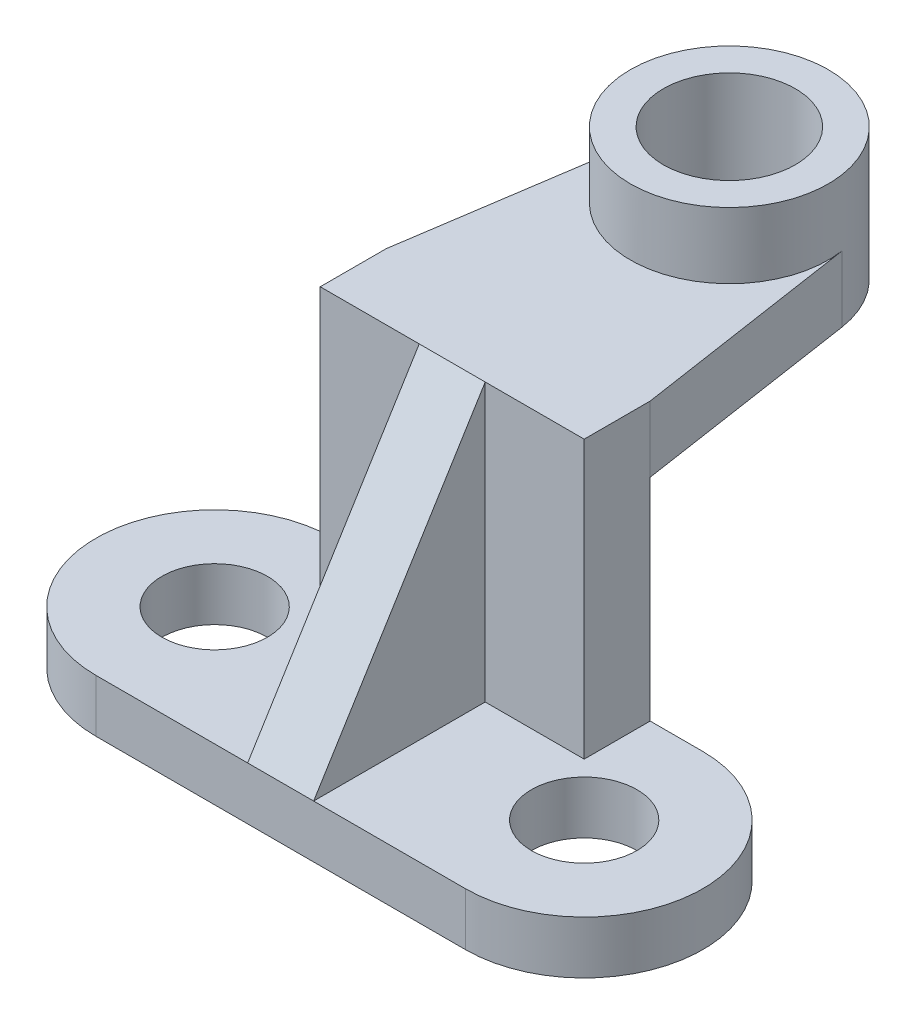
SolidWorks part; units mm, degrees
ref_plane "Front Plane" through (0, 0, 0) normal (0, 0, 1) x (1, 0, 0)
ref_plane "Top Plane" through (0, 0, 0) normal (0, 1, 0) x (1, 0, 0)
ref_plane "Right Plane" through (0, 0, 0) normal (1, 0, 0) x (0, 0, -1)
sketch "Sketch1" plane through (0, 0, 0) normal (0, 1, 0) x (1, 0, 0)
  line L0 (-28, 0) -> (28, 0) construction
  line L1 (-28, 18) -> (28, 18)
  line L2 (-28, -18) -> (28, -18)
  arc A0 (-28, 18) -> (-28, -18) centre (-28, 0) ccw
  arc A1 (28, -18) -> (28, 18) centre (28, 0) ccw
  circle A2 centre (-28, 0) radius 8
  circle A3 centre (28, 0) radius 8
  point P3 (0, 0)
  dimension "D1" = 18
  dimension "D3" = 16
  dimension "D2" = 56
extrude "Boss-Extrude1" add sketch "Sketch1" along normal mid plane 8
sketch "Sketch2" plane through (0, 4, 0) normal (0, 1, 0) x (1, 0, 0)
  line L0 (28, 18) -> (-28, 18) construction
  line L1 (-20, 8) -> (20, 8)
  line L2 (-20, 8) -> (-20, 18)
  line L3 (-20, 18) -> (20, 18)
  line L4 (20, 8) -> (20, 18)
  line L5 (-20, 8) -> (20, 18) construction
  line L6 (-20, 18) -> (20, 8) construction
  point P0 (0, 13)
  dimension "D1" = 40
  dimension "D2" = 10
extrude "Boss-Extrude2" add sketch "Sketch2" along normal blind 32
ref_plane "Plane1" through (0, 46, 0) normal (0, 1, 0) x (1, 0, 0)
sketch "Sketch3" plane through (0, 46, 0) normal (0, 1, 0) x (1, 0, 0)
  circle A0 centre (0, 50) radius 15
  circle A1 centre (0, 50) radius 10
  dimension "D1" = 30
  dimension "D2" = 20
  dimension "D3" = 50
extrude "Boss-Extrude3" add sketch "Sketch3" along normal mid plane 20 separate body
sketch "Sketch4" plane through (0, 46, 0) normal (0, 1, 0) x (1, 0, 0)
  line L0 (20, 8) -> (20, 18) construction
  line L1 (-20, 18) -> (-20, 8) construction
  line L2 (-20, 8) -> (20, 8) construction
  line L3 (20, 8) -> (20, 18)
  line L4 (-20, 18) -> (-20, 8)
  line L5 (-20, 8) -> (20, 8)
  line L6 (-20, 18) -> (-14.832, 52.2387)
  line L7 (20, 18) -> (14.832, 52.2387)
  circle A1 centre (0, 50) radius 15 construction
  arc A3 (-14.832, 52.2387) -> (14.832, 52.2387) centre (0, 50) ccw
extrude "Boss-Extrude4" add sketch "Sketch4" against normal blind 10
sketch "Sketch5" plane through (0, 0, 0) normal (1, 0, 0) x (0, 0, -1)
  line L0 (8, 46) -> (-18, 4)
rib "Rib6" sketch "Sketch5" sketch "Sketch5" thickness 10 extrusion direction parallel to sketch draft on no parameters "D1"=10
